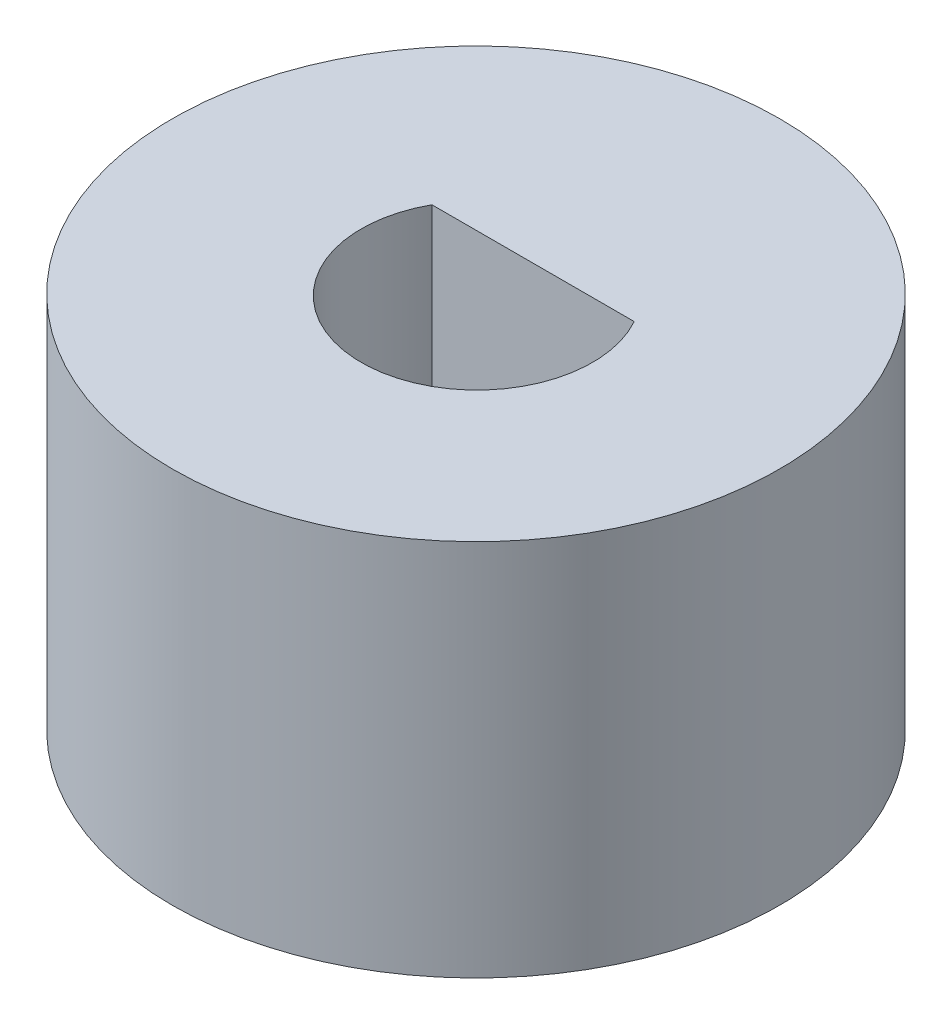
SolidWorks part; units mm, degrees
ref_plane "Front Plane" through (0, 0, 0) normal (0, 0, 1) x (1, 0, 0)
ref_plane "Top Plane" through (0, 0, 0) normal (0, 1, 0) x (1, 0, 0)
ref_plane "Right Plane" through (0, 0, 0) normal (1, 0, 0) x (0, 0, -1)
sketch "Sketch1" plane through (0, 0, 0) normal (0, 1, 0) x (1, 0, 0)
  line L2 (2.9211, 1.5599) -> (-2.8065, 1.5599)
  circle A0 centre (0, 0) radius 8.595
  arc A2 (2.9211, 1.5599) -> (-2.8065, 1.5599) centre (0.0573, -0.0318) cw
  dimension "D1" = 6.5528
extrude "Boss-Extrude1" add sketch "Sketch1" along normal blind 9.7
sketch "Sketch2" plane through (0, 0, 0) normal (0, -1, 0) x (1, 0, 0)
  circle A0 centre (0, 0) radius 8.595
extrude "Boss-Extrude3" add sketch "Sketch2" along normal blind 1
